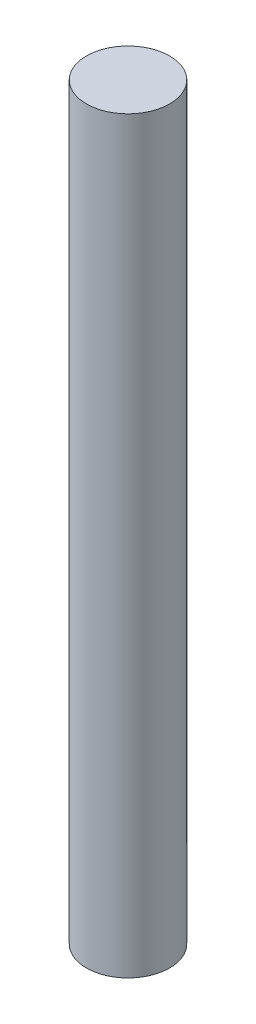
SolidWorks part; units mm, degrees
ref_plane "Front Plane" through (0, 0, 0) normal (0, 0, 1) x (1, 0, 0)
ref_plane "Top Plane" through (0, 0, 0) normal (0, 1, 0) x (1, 0, 0)
ref_plane "Right Plane" through (0, 0, 0) normal (1, 0, 0) x (0, 0, -1)
sketch "Sketch1" plane through (0, 0, 0) normal (0, 1, 0) x (1, 0, 0)
  circle A0 centre (0, 0) radius 2.5
  dimension "D1" = 5
extrude "Boss-Extrude1" add sketch "Sketch1" along normal blind 45
